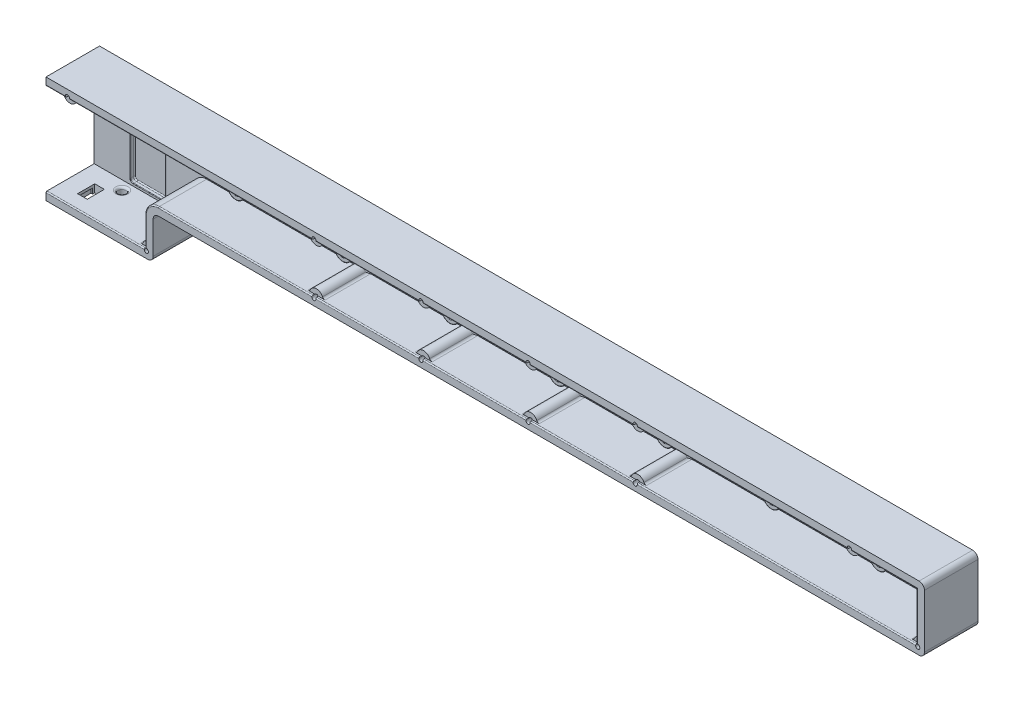
SolidWorks part; units mm, degrees
ref_plane "Front Plane" through (0, 0, 0) normal (0, 0, 1) x (1, 0, 0)
ref_plane "Top Plane" through (0, 0, 0) normal (0, 1, 0) x (1, 0, 0)
ref_plane "Right Plane" through (0, 0, 0) normal (1, 0, 0) x (0, 0, -1)
sketch "Sketch1" plane through (0, 0, 0) normal (0, 0, 1) x (1, 0, 0)
  line L0 (-50, 0) -> (0, 0) construction
  line L1 (-420, -70) -> (420, -70)
  line L2 (-420, -70) -> (-420, 70)
  line L3 (-420, 70) -> (420, 70)
  line L4 (420, -70) -> (420, 70)
  line L5 (-420, -70) -> (420, 70) construction
  line L6 (-420, 70) -> (420, -70) construction
  line L7 (0, 0) -> (50, 0) construction
  line L8 (250, 0) -> (350, 0) construction
  line L9 (333.7, -57.5) -> (333.7, 17.5)
  line L14 (334, -40) -> (350, 0) construction
  line L15 (334, 40) -> (334.4358, 38.9104) construction
  line L16 (336.5, 20.3) -> (363.5, 20.3)
  line L17 (366.3, -57.5) -> (366.3, 17.5)
  line L18 (336.5, -60.3) -> (363.5, -60.3)
  line L21 (365.5642, -38.9104) -> (366, -40) construction
  line L22 (365.5642, 38.9104) -> (366, 40) construction
  circle A0 centre (-350, 0) radius 4.15
  circle A1 centre (-250, 0) radius 4.15
  circle A2 centre (-150, 0) radius 4.15
  circle A3 centre (-50, 0) radius 4.15
  circle A4 centre (50, 0) radius 4.15
  circle A5 centre (150, 0) radius 4.15
  circle A6 centre (250, 0) radius 4.15
  circle A8 centre (350, 0) radius 4.15 [skipped]
  arc A13 (333.7, 17.5) -> (336.5, 20.3) centre (336.5, 17.5) cw
  arc A14 (363.5, 20.3) -> (366.3, 17.5) centre (363.5, 17.5) cw
  arc A15 (363.5, -60.3) -> (366.3, -57.5) centre (363.5, -57.5) ccw
  arc A16 (336.5, -60.3) -> (333.7, -57.5) centre (336.5, -57.5) cw
  point P0 (0, 0)
  dimension "D3" = 8.3
  dimension "D5" = 80
  dimension "D1" = 840
  dimension "D2" = 140
  dimension "D6" = 32
  dimension "D4" = 8
extrude "Boss-Extrude1" add sketch "Sketch1" along normal blind 5
sketch "Sketch2" plane through (0, 0, 5) normal (0, 0, 1) x (1, 0, 0)
  circle A0 centre (-350, 0) radius 8
  circle A1 centre (-350, 0) radius 4.15
extrude "Boss-Extrude3" add sketch "Sketch2" along normal blind 18
pattern_linear "LPattern1" count 7 spacing 100 along (1, 0, 0) of "Boss-Extrude3"
sketch "Sketch4" plane through (0, 0, 0) normal (0, 0, -1) x (-1, 0, 0)
  line L1 (-372.738, 24.1165) -> (-327.1271, 24.1165)
  line L2 (-372.738, 24.1165) -> (-372.738, -63.8212)
  line L3 (-372.738, -63.8212) -> (-327.1271, -63.8212)
  line L4 (-327.1271, 24.1165) -> (-327.1271, -63.8212)
extrude "Boss-Extrude4" add sketch "Sketch4" against normal blind 1
sketch "Sketch5" plane through (0, 70, 0) normal (0, 1, 0) x (1, 0, 0)
  line L4 (420, 0) -> (-420, 0)
  line L5 (-420, 0) -> (-420, -5)
  line L6 (-420, -5) -> (420, -5)
  line L7 (420, -5) -> (420, 0)
  line L8 (420, 0) -> (-420, 0)
  line L9 (-420, 0) -> (-420, -5)
  line L10 (-420, -5) -> (420, -5)
  line L11 (420, -5) -> (420, 0)
  dimension "D1" = 0
extrude "Cut-Extrude1" cut sketch "Sketch5" against normal blind 40
sketch "Sketch6" plane through (0, 0, 5) normal (0, 0, 1) x (1, 0, 0)
  line L0 (420, -70) -> (420, 30) construction
  line L1 (-420, -70) -> (300, -70)
  line L2 (-420, -70) -> (-420, -30)
  line L3 (-420, -30) -> (300, -30)
  line L4 (300, -70) -> (300, -30)
  dimension "D1" = 40
  dimension "D2" = 120
extrude "Cut-Extrude2" cut sketch "Sketch6" against normal through all
fillet "Fillet1" radius 5 4 edges at (300, -70, 2.5) (300, -30, 2.5) (-420, -30, 2.5) (-420, 30, 2.5)
fillet "Fillet2" radius 0.5 29 edges at (365.4799, -59.4799, 5) (350, -60.3, 5) (334.5201, -59.4799, 5) (333.7, -20, 5) (334.5201, 19.4799, 5) (350, 20.3, 5) (365.4799, 19.4799, 5) (-145.85, 0, 23) (-142, 0, 23) (-245.85, 0, 23) (-242, 0, 23) (366.3, -20, 5) (254.15, 0, 23) (258, 0, 23) (154.15, 0, 23) (158, 0, 23) (54.15, 0, 23) (58, 0, 23) (-45.85, 0, 23) (-42, 0, 23) (242, 0, 5) (142, 0, 5) (42, 0, 5) (-58, 0, 5) (-158, 0, 5) (-258, 0, 5) (-345.85, 0, 23) (-342, 0, 23) (-358, 0, 5)
fillet "Fillet3" radius 1 8 edges at (334.5201, 19.4799, 1) (333.7, -20, 1) (334.5201, -59.4799, 1) (350, -60.3, 1) (365.4799, -59.4799, 1) (366.3, -20, 1) (365.4799, 19.4799, 1) (350, 20.3, 1)
sketch "Sketch8" plane through (0, 0, 5) normal (0, 0, 1) x (1, 0, 0)
  line L0 (412.625, -62.625) -> (412.625, 22.625)
  line L1 (412.625, 22.625) -> (-412.625, 22.625)
  line L2 (-412.625, 22.625) -> (-412.625, -22.625)
  line L3 (-412.625, -22.625) -> (295, -22.625)
  line L4 (307.375, -35) -> (307.375, -62.625)
  line L5 (307.375, -62.625) -> (412.625, -62.625)
  line L6 (300, -35) -> (300, -65)
  line L7 (305, -70) -> (420, -70)
  line L8 (420, -70) -> (420, 30)
  line L9 (420, 30) -> (-415, 30)
  line L10 (-420, 25) -> (-420, -25)
  line L11 (-415, -30) -> (295, -30)
  line L12 (300, -35) -> (300, -65)
  line L13 (305, -70) -> (420, -70)
  line L14 (420, -70) -> (420, 30)
  line L15 (420, 30) -> (-415, 30)
  line L16 (-420, 25) -> (-420, -25)
  line L17 (-415, -30) -> (295, -30)
  arc A0 (-412.625, 22.625) -> (-412.625, 22.625) centre (-412.625, 22.625) ccw
  arc A1 (-412.625, -22.625) -> (-412.625, -22.625) centre (-412.625, -22.625) ccw
  arc A2 (307.375, -35) -> (295, -22.625) centre (295, -35) ccw
  arc A3 (307.375, -62.625) -> (307.375, -62.625) centre (307.375, -62.625) ccw
  arc A4 (300, -65) -> (305, -70) centre (305, -65) ccw
  arc A5 (-415, 30) -> (-420, 25) centre (-415, 25) ccw
  arc A6 (-420, -25) -> (-415, -30) centre (-415, -25) ccw
  arc A7 (300, -35) -> (295, -30) centre (295, -35) ccw
  arc A8 (300, -65) -> (305, -70) centre (305, -65) ccw
  arc A9 (-415, 30) -> (-420, 25) centre (-415, 25) ccw
  arc A10 (-420, -25) -> (-415, -30) centre (-415, -25) ccw
  arc A11 (300, -35) -> (295, -30) centre (295, -35) ccw
  dimension "D1" = 0
  dimension "D2" = 7.375
extrude "Boss-Extrude5" add sketch "Sketch8" along normal blind 45
ref_plane "Plane1" through (-140, 0, 0) normal (-1, 0, 0) x (0, 0, 1)
ref_plane "Plane2" through (140, 0, 0) normal (-1, 0, 0) x (0, 0, 1)
fillet "Fillet4" radius 1 3 edges at (307.375, -48.8125, 50) (303.7504, -26.2496, 50) (-58.8125, -22.625, 50)
sketch "Sketch10" plane through (0, 0, 50) normal (0, 0, 1) x (1, 0, 0)
  line L0 (412.625, -62.625) -> (412.625, 22.625) construction
  line L1 (412.625, 22.625) -> (420, 22.625)
  line L2 (412.625, 22.625) -> (412.625, -62.625)
  line L3 (412.625, -62.625) -> (420, -62.625)
  line L4 (420, 22.625) -> (420, -62.625)
  line L5 (412.625, -62.625) -> (412.625, 22.625) construction
  line L6 (420, -70) -> (420, 30) construction
extrude "Cut-Extrude3" cut sketch "Sketch10" against normal up to surface (45 mm away) up to face at (130.3304, -22.5267, 5)
fillet "Fillet5" radius 1 3 edges at (-412.625, -0.5, 50) (3.6875, 22.625, 50) (363.1875, -62.625, 50)
sketch "Sketch11" plane through (0, 0, 0) normal (0, 0, -1) x (-1, 0, 0)
  circle A0 centre (-250, 0) radius 4.15
  circle A1 centre (-150, 0) radius 4.15
  circle A2 centre (-50, 0) radius 4.15
  circle A3 centre (50, 0) radius 4.15
  circle A4 centre (150, 0) radius 4.15
  circle A5 centre (250, 0) radius 4.15
  circle A6 centre (350, 0) radius 4.15
  dimension "D1" = 7
extrude "Boss-Extrude6" add sketch "Sketch11" against normal blind 5
mirror "Mirror1" about plane through (420, -70, 5) normal (-1, 0, 0) of bodies 110
delete or keep bodies "Body-Delete/Keep 2" type delete bodies bodies 110
sketch "Sketch12" plane through (420, 0, 0) normal (-1, 0, 0) x (0, 0, 1)
  line L8 (50, 23.625) -> (50, 30)
  line L9 (50, 30) -> (0, 30)
  line L10 (0, 30) -> (0, -70)
  line L11 (0, -70) -> (50, -70)
  line L12 (50, -70) -> (50, -63.625)
  line L13 (49, -62.625) -> (5, -62.625)
  line L14 (5, -62.625) -> (5, 22.625)
  line L15 (5, 22.625) -> (49, 22.625)
  line L16 (50, 23.625) -> (50, 30)
  line L17 (50, 30) -> (0, 30)
  line L18 (0, 30) -> (0, -70)
  line L19 (0, -70) -> (50, -70)
  line L20 (50, -70) -> (50, -63.625)
  line L21 (49, -62.625) -> (5, -62.625)
  line L22 (5, -62.625) -> (5, 22.625)
  line L23 (5, 22.625) -> (49, 22.625)
  arc A2 (50, -63.625) -> (49, -62.625) centre (49, -63.625) ccw
  arc A3 (49, 22.625) -> (50, 23.625) centre (49, 23.625) ccw
  arc A4 (50, -63.625) -> (49, -62.625) centre (49, -63.625) ccw
  arc A5 (49, 22.625) -> (50, 23.625) centre (49, 23.625) ccw
  dimension "D1" = 0
extrude "Cut-Extrude4" cut sketch "Sketch12" against normal blind 20
sketch "Sketch13" plane through (0, -70, 0) normal (0, -1, 0) x (1, 0, 0)
  line L0 (535, 50) -> (440, 50) construction
  line L1 (455, 35) -> (467, 35)
  line L2 (455, 35) -> (455, 23)
  line L3 (455, 23) -> (467, 23)
  line L4 (467, 35) -> (467, 23)
  line L5 (440, 0) -> (440, 50) construction
  point P6 (455, 29)
  dimension "D1" = 12
  dimension "D2" = 12
  dimension "D3" = 15
  dimension "D4" = 15
extrude "Cut-Extrude5" cut sketch "Sketch13" against normal blind 5
sketch "Sketch14" plane through (0, -70, 0) normal (0, -1, 0) x (1, 0, 0)
  line L0 (467, 35) -> (455, 35) construction
  line L1 (456.5, 37) -> (465.5, 37)
  line L2 (456.5, 37) -> (456.5, 21)
  line L3 (456.5, 21) -> (465.5, 21)
  line L4 (465.5, 37) -> (465.5, 21)
  line L5 (455, 35) -> (455, 23) construction
  point P4 (461, 35)
  point P5 (455, 29)
  point P8 (461, 37)
  point P11 (456.5, 29)
  dimension "D1" = 9
  dimension "D2" = 16
extrude "Cut-Extrude6" cut sketch "Sketch14" against normal up to next
sketch "Sketch20" plane through (0, 0, 50) normal (0, 0, 1) x (1, 0, 0)
  line L0 (440, 30) -> (1255, 30) construction
  line L1 (1255, -30) -> (545, -30) construction
  line L2 (540, -35) -> (540, -65) construction
  line L3 (535, -70) -> (440, -70) construction
  line L5 (440, 23.625) -> (440, 30) construction
  line L12 (1255, 30) -> (440, 30)
  line L13 (440, 30) -> (440, 23.625)
  line L14 (440, 23.625) -> (1253.625, 23.625)
  line L15 (1253.625, 23.625) -> (1253.625, -23.625)
  line L16 (1253.625, -23.625) -> (545, -23.625)
  line L17 (533.625, -35) -> (533.625, -63.625)
  line L18 (533.625, -63.625) -> (440, -63.625)
  line L19 (440, -63.625) -> (440, -70)
  line L20 (440, -70) -> (535, -70)
  line L21 (540, -65) -> (540, -35)
  line L22 (545, -30) -> (1255, -30)
  line L23 (1260, -25) -> (1260, 25)
  line L35 (1260, -25) -> (1260, 25)
  circle A0 centre (790, 23.75) radius 1.95
  circle A1 centre (790, -23.75) radius 1.95
  circle A4 centre (460, 23.75) radius 1.95
  arc A5 (545, -23.625) -> (533.625, -35) centre (545, -35) ccw
  arc A6 (535, -70) -> (540, -65) centre (535, -65) ccw
  arc A7 (545, -30) -> (540, -35) centre (545, -35) ccw
  arc A8 (1255, -30) -> (1260, -25) centre (1255, -25) ccw
  arc A9 (1260, 25) -> (1255, 30) centre (1255, 25) ccw
  arc A11 (535, -70) -> (540, -65) centre (535, -65) ccw
  arc A12 (545, -30) -> (540, -35) centre (545, -35) ccw
  arc A13 (1255, -30) -> (1260, -25) centre (1255, -25) ccw
  arc A14 (1260, 25) -> (1255, 30) centre (1255, 25) ccw
  circle A15 centre (533.75, -63.75) radius 1.95
  circle A16 centre (690, 23.75) radius 1.95
  circle A17 centre (890, -23.75) radius 1.95
  circle A18 centre (990, 23.75) radius 1.95
  circle A19 centre (690, -23.75) radius 1.95
  circle A20 centre (890, 23.75) radius 1.95
  circle A21 centre (990, -23.75) radius 1.95
  circle A22 centre (1190, 23.75) radius 1.95
  circle A23 centre (1253.75, -23.75) radius 1.95
  point P13 (890, 0)
  point P28 (790, 0)
  point P44 (690, 0)
  point P45 (549.6314, -62.5466)
  point P46 (689.7552, 26.25)
  point P49 (990, 0)
  point P63 (1190, 0)
  dimension "D3" = 20
  dimension "D4" = 3.9
  dimension "D5" = 6.25
  dimension "D2" = 6.25
  dimension "D6" = 6.25
  dimension "D7" = 6.25
  dimension "D8" = 6.25
  dimension "D9" = 6.25
  dimension "D10" = 6.25
  dimension "D11" = 6.25
  dimension "D1" = 0
extrude "Cut-Extrude8" cut sketch "Sketch20" against normal blind 26 contours A4 | A15 | A16 | A19 | A20 | A17 | A18 | A21 | A22 | A23 | A1 | A0
ref_plane "Plane5" through (700, 0, 0) normal (-1, 0, 0) x (0, 0, 1)
ref_plane "Plane6" through (980, 0, 0) normal (-1, 0, 0) x (0, 0, 1)
ref_plane "Plane7" through (0, 0, 47.5) normal (0, 0, 1) x (1, 0, 0)
sketch "Sketch22" plane through (0, 0, 47.5) normal (0, 0, 1) x (1, 0, 0)
  circle A0 centre (460, 23.75) radius 1.95
  circle A1 centre (460, 23.75) radius 6.25
  circle A2 centre (690, 23.75) radius 1.95
  circle A3 centre (690, 23.75) radius 6.25
  circle A4 centre (790, 23.75) radius 1.95
  circle A5 centre (790, 23.75) radius 6.25
  circle A6 centre (890, 23.75) radius 1.95
  circle A7 centre (890, 23.75) radius 6.25
  circle A8 centre (990, 23.75) radius 1.95
  circle A9 centre (990, 23.75) radius 6.25
  circle A10 centre (1190, 23.75) radius 1.95
  circle A11 centre (1190, 23.75) radius 6.25
  circle A12 centre (1253.75, -23.75) radius 1.95
  circle A13 centre (1253.75, -23.75) radius 6.25
  circle A14 centre (990, -23.75) radius 1.95
  circle A16 centre (990, -23.75) radius 6.25
  circle A17 centre (890, -23.75) radius 1.95
  circle A18 centre (890, -23.75) radius 6.25
  circle A19 centre (790, -23.75) radius 1.95
  circle A20 centre (790, -23.75) radius 6.25
  circle A21 centre (690, -23.75) radius 1.95
  circle A22 centre (690, -23.75) radius 6.25
  circle A23 centre (533.75, -63.75) radius 1.95
  circle A24 centre (533.75, -63.75) radius 6.25
extrude "Boss-Extrude8" add sketch "Sketch22" against normal up to surface (42.5 mm away) up to face at (1198.5, 0, 5)
sketch "Sketch23" plane through (0, 0, 5) normal (0, 0, 1) x (1, 0, 0)
  line L1 (461.5928, 22.625) -> (458.4072, 22.625)
  line L2 (461.5928, 22.625) -> (458.4072, 22.625)
  line L3 (691.5928, 22.625) -> (688.4072, 22.625)
  line L4 (691.5928, 22.625) -> (688.4072, 22.625)
  line L5 (791.5928, 22.625) -> (788.4072, 22.625)
  line L6 (791.5928, 22.625) -> (788.4072, 22.625)
  line L7 (891.5928, 22.625) -> (888.4072, 22.625)
  line L8 (891.5928, 22.625) -> (888.4072, 22.625)
  line L9 (991.5928, 22.625) -> (988.4072, 22.625)
  line L10 (991.5928, 22.625) -> (988.4072, 22.625)
  line L11 (1191.5928, 22.625) -> (1188.4072, 22.625)
  line L12 (1191.5928, 22.625) -> (1188.4072, 22.625)
  line L13 (988.4072, -22.625) -> (991.5928, -22.625)
  line L14 (1252.1572, -22.625) -> (1252.625, -22.625)
  line L15 (1252.625, -22.625) -> (1252.625, -22.1572)
  line L16 (1252.1572, -22.625) -> (1252.625, -22.625)
  line L17 (1252.625, -22.625) -> (1252.625, -22.1572)
  line L18 (988.4072, -22.625) -> (991.5928, -22.625)
  line L19 (888.4072, -22.625) -> (891.5928, -22.625)
  line L20 (888.4072, -22.625) -> (891.5928, -22.625)
  line L21 (788.4072, -22.625) -> (791.5928, -22.625)
  line L22 (788.4072, -22.625) -> (791.5928, -22.625)
  line L23 (688.4072, -22.625) -> (691.5928, -22.625)
  line L24 (688.4072, -22.625) -> (691.5928, -22.625)
  line L26 (532.1572, -62.625) -> (532.625, -62.625)
  line L27 (532.625, -62.625) -> (532.625, -62.1572)
  line L28 (532.1572, -62.625) -> (532.625, -62.625)
  line L29 (532.625, -62.625) -> (532.625, -62.1572)
  arc A1 (458.4072, 22.625) -> (461.5928, 22.625) centre (460, 23.75) ccw
  arc A2 (458.4072, 22.625) -> (461.5928, 22.625) centre (460, 23.75) ccw
  arc A3 (688.4072, 22.625) -> (691.5928, 22.625) centre (690, 23.75) ccw
  arc A4 (688.4072, 22.625) -> (691.5928, 22.625) centre (690, 23.75) ccw
  arc A5 (788.4072, 22.625) -> (791.5928, 22.625) centre (790, 23.75) ccw
  arc A6 (788.4072, 22.625) -> (791.5928, 22.625) centre (790, 23.75) ccw
  arc A7 (888.4072, 22.625) -> (891.5928, 22.625) centre (890, 23.75) ccw
  arc A8 (888.4072, 22.625) -> (891.5928, 22.625) centre (890, 23.75) ccw
  arc A9 (988.4072, 22.625) -> (991.5928, 22.625) centre (990, 23.75) ccw
  arc A10 (988.4072, 22.625) -> (991.5928, 22.625) centre (990, 23.75) ccw
  arc A11 (1188.4072, 22.625) -> (1191.5928, 22.625) centre (1190, 23.75) ccw
  arc A12 (1188.4072, 22.625) -> (1191.5928, 22.625) centre (1190, 23.75) ccw
  arc A13 (1252.625, -22.1572) -> (1252.1572, -22.625) centre (1253.75, -23.75) ccw
  arc A14 (1252.625, -22.1572) -> (1252.1572, -22.625) centre (1253.75, -23.75) ccw
  arc A15 (991.5928, -22.625) -> (988.4072, -22.625) centre (990, -23.75) ccw
  arc A16 (991.5928, -22.625) -> (988.4072, -22.625) centre (990, -23.75) ccw
  arc A17 (891.5928, -22.625) -> (888.4072, -22.625) centre (890, -23.75) ccw
  arc A18 (891.5928, -22.625) -> (888.4072, -22.625) centre (890, -23.75) ccw
  arc A19 (791.5928, -22.625) -> (788.4072, -22.625) centre (790, -23.75) ccw
  arc A20 (791.5928, -22.625) -> (788.4072, -22.625) centre (790, -23.75) ccw
  arc A21 (691.5928, -22.625) -> (688.4072, -22.625) centre (690, -23.75) ccw
  arc A22 (691.5928, -22.625) -> (688.4072, -22.625) centre (690, -23.75) ccw
  arc A23 (532.625, -62.1572) -> (532.1572, -62.625) centre (533.75, -63.75) ccw
  arc A24 (532.625, -62.1572) -> (532.1572, -62.625) centre (533.75, -63.75) ccw
  dimension "D1" = 0
  dimension "D2" = 0
  dimension "D3" = 0
  dimension "D4" = 0
  dimension "D5" = 0
  dimension "D6" = 0
  dimension "D7" = 0
  dimension "D8" = 0
  dimension "D9" = 0
  dimension "D10" = 0
  dimension "D11" = 0
  dimension "D12" = 0
extrude "Boss-Extrude9" add sketch "Sketch23" along normal up to surface (19 mm away) up to face at (460, 24.1625, 24)
fillet "Fillet6" radius 2.5 36 edges at (890, 17.5, 5) (990, 17.5, 5) (1190, 17.5, 5) (1252.625, -17.6021, 26.25) (1249.3306, -19.3306, 5) (990, -17.5, 5) (890, -17.5, 5) (532.625, -57.6021, 26.25) (896.1479, -22.625, 26.25) (883.8521, -22.625, 26.25) (996.1479, -22.625, 26.25) (983.8521, -22.625, 26.25) (1247.6021, -22.625, 26.25) (796.1479, -22.625, 26.25) (783.8521, -22.625, 26.25) (696.1479, -22.625, 26.25) (683.8521, -22.625, 26.25) (1183.8521, 22.625, 26.25) (1196.1479, 22.625, 26.25) (983.8521, 22.625, 26.25) (996.1479, 22.625, 26.25) (883.8521, 22.625, 26.25) (896.1479, 22.625, 26.25) (783.8521, 22.625, 26.25) (796.1479, 22.625, 26.25) (683.8521, 22.625, 26.25) (696.1479, 22.625, 26.25) (453.8521, 22.625, 26.25) (466.1479, 22.625, 26.25) (460, 17.5, 5) (529.3306, -59.3306, 5) (527.6021, -62.625, 26.25) (690, -17.5, 5) (790, -17.5, 5) (690, 17.5, 5) (790, 17.5, 5)
sketch "Sketch24" plane through (0, -70, 0) normal (0, -1, 0) x (1, 0, 0)
  circle A0 centre (474.4991, 13.5423) radius 3.75
  dimension "D1" = 7.5
extrude "Cut-Extrude9" cut sketch "Sketch24" against normal up to next
fillet "Fillet7" radius 2 1 edges at (474.4991, -62.625, 17.2923)
